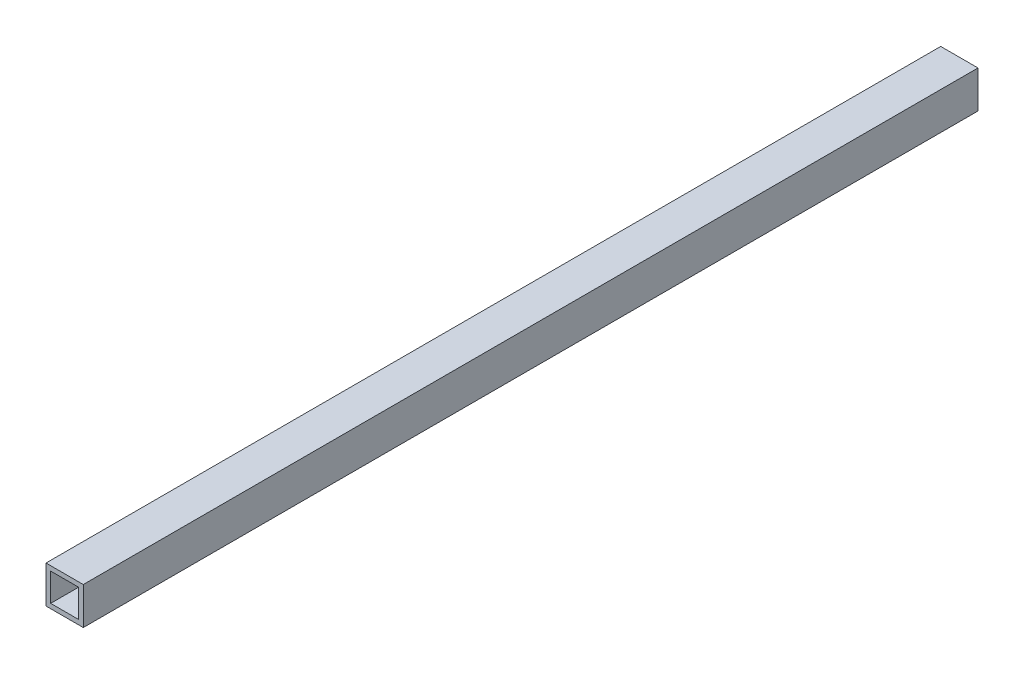
SolidWorks part; units mm, degrees
ref_plane "Front Plane" through (0, 0, 0) normal (0, 0, 1) x (1, 0, 0)
ref_plane "Top Plane" through (0, 0, 0) normal (0, 1, 0) x (1, 0, 0)
ref_plane "Right Plane" through (0, 0, 0) normal (1, 0, 0) x (0, 0, -1)
sketch "Sketch1" plane through (0, 0, 0) normal (0, 0, 1) x (1, 0, 0)
  line L0 (-9.525, 9.525) -> (9.525, 9.525)
  line L1 (-12.7, -12.7) -> (12.7, -12.7)
  line L2 (-12.7, -12.7) -> (-12.7, 12.7)
  line L3 (-12.7, 12.7) -> (12.7, 12.7)
  line L4 (12.7, -12.7) -> (12.7, 12.7)
  line L5 (-12.7, -12.7) -> (12.7, 12.7) construction
  line L6 (-12.7, 12.7) -> (12.7, -12.7) construction
  line L7 (9.525, -9.525) -> (9.525, 9.525)
  line L8 (-9.525, -9.525) -> (9.525, -9.525)
  line L9 (-9.525, -9.525) -> (-9.525, 9.525)
  point P0 (0, 0)
  dimension "D1" = 25.4
  dimension "D2" = 3.175
extrude "Boss-Extrude1" add sketch "Sketch1" along normal blind 609.6
